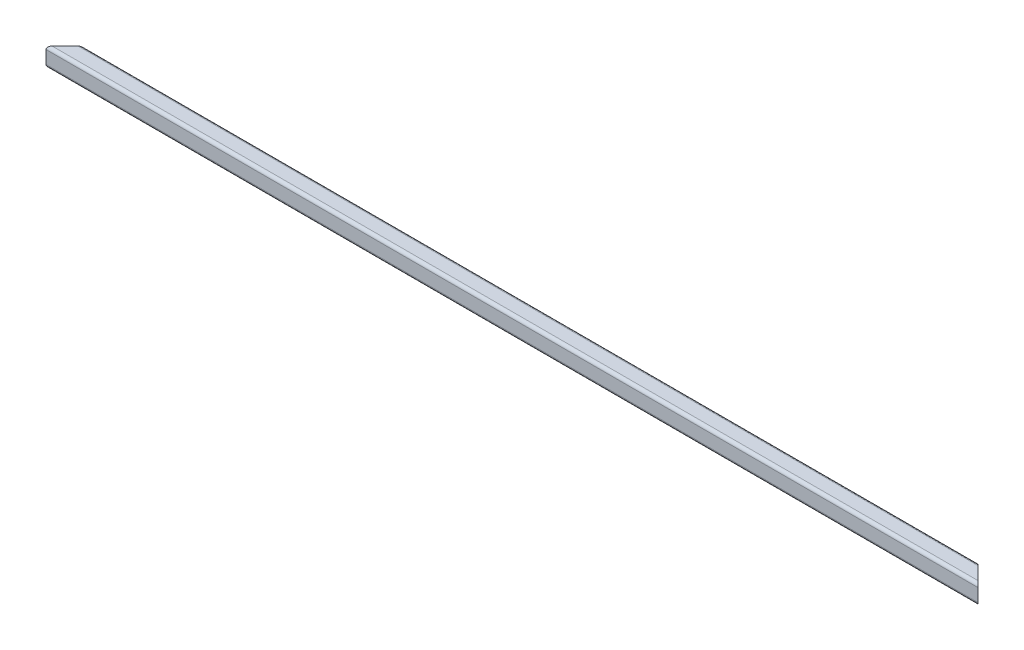
SolidWorks part; units mm, degrees
ref_plane "Front Plane" through (0, 0, 0) normal (0, 0, 1) x (1, 0, 0)
ref_plane "Top Plane" through (0, 0, 0) normal (0, 1, 0) x (1, 0, 0)
ref_plane "Right Plane" through (0, 0, 0) normal (1, 0, 0) x (0, 0, -1)
sketch "Sketch1" plane through (0, 0, 0) normal (0, 1, 0) x (1, 0, 0)
  line L0 (0, 0) -> (1960, 0)
  dimension "D1" = 1960
other "Tube (square) 40 X 40 X 3.2(5)"
ref_plane "Plane1" through (0, 0, 0) normal (1, 0, 0) x (0, 0, -1)
sketch "Sketch12" plane through (0, 0, 0) normal (1, 0, 0) x (0, 0, -1)
  line L0 (-13.6, -16.8) -> (13.6, -16.8)
  line L1 (-16.8, -13.6) -> (-16.8, 13.6)
  line L2 (13.6, 16.8) -> (-13.6, 16.8)
  line L3 (16.8, 13.6) -> (16.8, -13.6)
  line L4 (-13.6, -20) -> (13.6, -20)
  line L5 (-20, -13.6) -> (-20, 13.6)
  line L6 (13.6, 20) -> (-13.6, 20)
  line L7 (20, 13.6) -> (20, -13.6)
  line L8 (-20, 0) -> (-16.8, 0) construction
  line L9 (-16.8, 0) -> (16.8, 0) construction
  line L10 (16.8, 0) -> (20, 0) construction
  line L12 (0, 20) -> (0, 16.8) construction
  line L13 (0, 16.8) -> (0, -16.8) construction
  line L14 (0, -16.8) -> (0, -20) construction
  arc A0 (20, 13.6) -> (13.6, 20) centre (13.6, 13.6) ccw
  arc A1 (13.6, -20) -> (20, -13.6) centre (13.6, -13.6) ccw
  arc A2 (-20, -13.6) -> (-13.6, -20) centre (-13.6, -13.6) ccw
  arc A3 (-13.6, 20) -> (-20, 13.6) centre (-13.6, 13.6) ccw
  arc A4 (-13.6, 16.8) -> (-16.8, 13.6) centre (-13.6, 13.6) ccw
  arc A5 (16.8, 13.6) -> (13.6, 16.8) centre (13.6, 13.6) ccw
  arc A6 (13.6, -16.8) -> (16.8, -13.6) centre (13.6, -13.6) ccw
  arc A7 (-16.8, -13.6) -> (-13.6, -16.8) centre (-13.6, -13.6) ccw
  point P2 (-20, 20)
  point P33 (-20, -20)
  point P34 (20, -20)
  point P36 (20, 20)
  point P37 (0, 0)
  dimension "D1" = 6.4
  dimension "Thickness" = 3.2
  dimension "V_leg" = 40
  dimension "H_leg" = 40
ref_plane "Plane2" through (0, 20, 0) normal (0, 1, 0) x (1, 0, 0)
sketch "Sketch13" plane through (0, 20, 0) normal (0, 1, 0) x (1, 0, 0)
  line L1 (0, 13.6) -> (0, -13.6) construction
  line L3 (1960, 20) -> (1960, -20)
  line L4 (0, 20) -> (0, 13.6)
  line L5 (0, 13.6) -> (1960, 13.6)
  line L6 (1960, 13.6) -> (1960, 20)
  line L7 (1960, 20) -> (0, 20)
  line L11 (1960, 20) -> (1920, 20)
  line L12 (0, 20) -> (0, -20)
  line L13 (40, 20) -> (0, -20)
  line L20 (40, 20) -> (0, 20)
  line L23 (1920, 20) -> (1960, -20)
  dimension "D2" = 40
  dimension "D3" = 40
  dimension "D1" = 0
extrude "Cut-Extrude1" cut sketch "Sketch13" against normal through all
sketch "Sketch15" plane through (0, 0, 0) normal (0, 1, 0) x (1, 0, 0)
  line L0 (1940, 0) -> (980, 0) construction
  line L1 (980, 0) -> (20, 0) construction
  circle A5 centre (980, 0) radius 2
  circle A6 centre (20, 0) radius 2
  circle A7 centre (1940, 0) radius 2
  circle A8 centre (500, 0) radius 2
  circle A9 centre (1460, 0) radius 2
extrude "Cut-Extrude3" cut sketch "Sketch15" against normal through all
